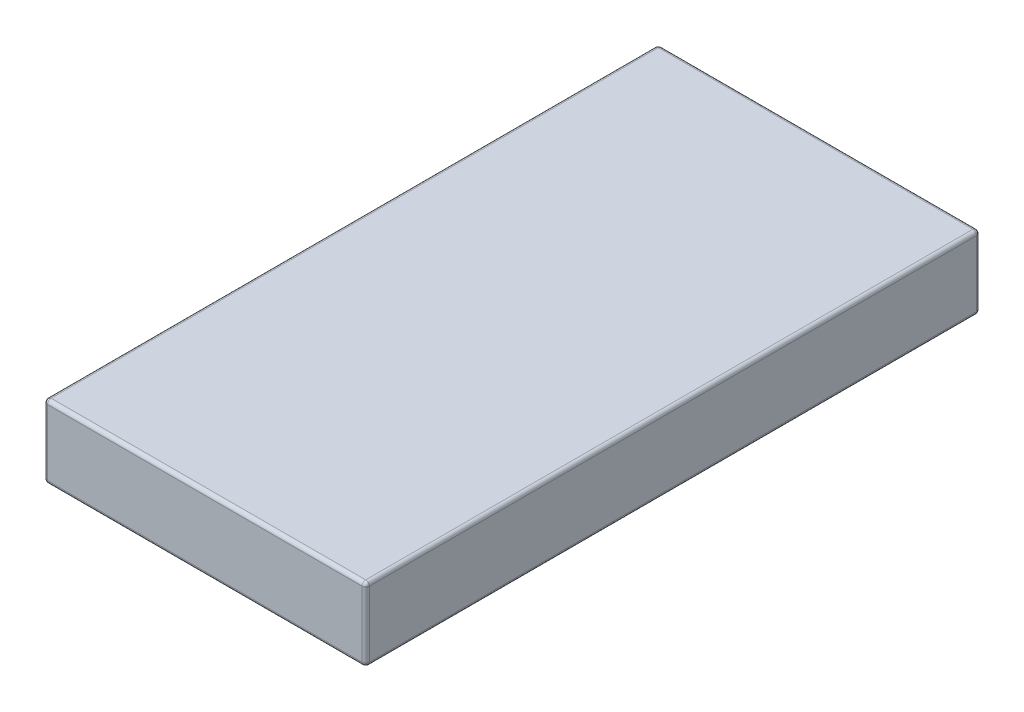
SolidWorks part; units mm, degrees
ref_plane "Alzado" through (0, 0, 0) normal (0, 0, 1) x (1, 0, 0)
ref_plane "Planta" through (0, 0, 0) normal (0, 1, 0) x (1, 0, 0)
ref_plane "Vista lateral" through (0, 0, 0) normal (1, 0, 0) x (0, 0, -1)
sketch "Croquis1" plane through (0, 0, 0) normal (0, 1, 0) x (1, 0, 0)
  line L1 (0, 0) -> (44, 0)
  line L2 (0, 0) -> (0, 84)
  line L3 (0, 84) -> (44, 84)
  line L4 (44, 0) -> (44, 84)
  dimension "D1" = 44
  dimension "D2" = 84
extrude "Saliente-Extruir1" add sketch "Croquis1" along normal blind 10
fillet "Redondeo2" radius 0.5 12 edges at (0, 5, -84) (44, 5, -84) (0, 5, 0) (44, 5, 0) (22, 0, 0) (44, 0, -42) (22, 0, -84) (0, 0, -42) (22, 10, -84) (44, 10, -42) (22, 10, 0) (0, 10, -42)
